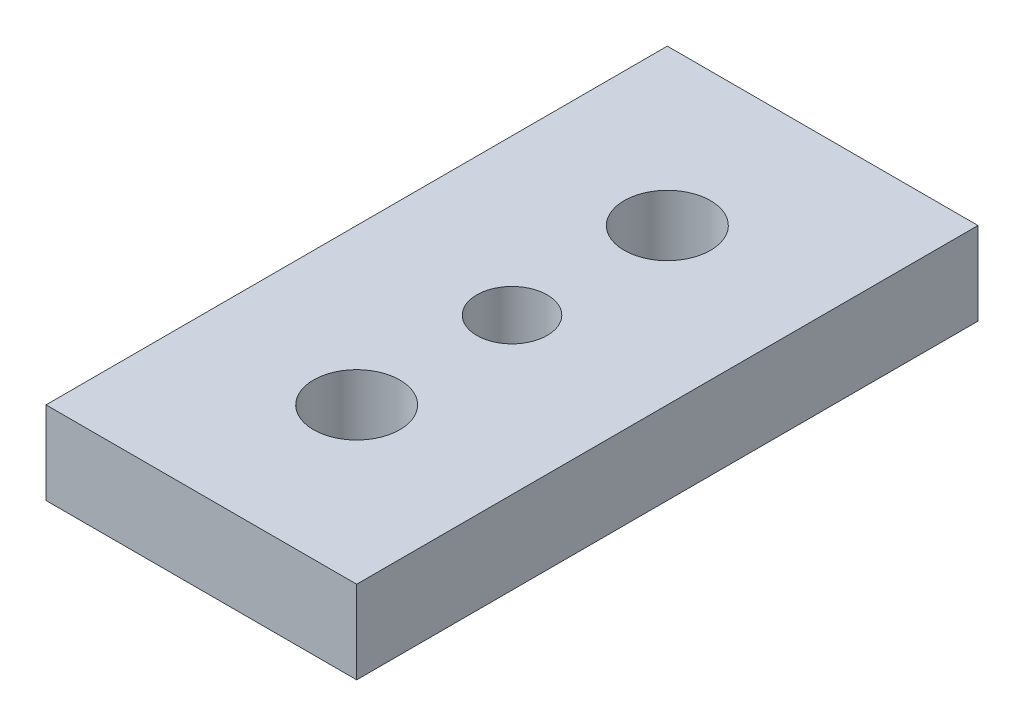
SolidWorks part; units mm, degrees
ref_plane "前视基准面" through (0, 0, 0) normal (0, 0, 1) x (1, 0, 0)
ref_plane "上视基准面" through (0, 0, 0) normal (0, 1, 0) x (1, 0, 0)
ref_plane "右视基准面" through (0, 0, 0) normal (1, 0, 0) x (0, 0, -1)
sketch "草图1" plane through (0, 0, 0) normal (0, 1, 0) x (1, 0, 0)
  line B0 (0, 0) -> (45, 0)
  line B1 (45, 0) -> (45, 90)
  line B2 (45, 90) -> (0, 90)
  line B3 (0, 90) -> (0, 0)
  circle B4 centre (22.5, 67.5) radius 6.25
  circle B5 centre (22.5, 22.5) radius 6.25
sketch_block_instance "A$C5C6430CE-1"
sketch_block "A$C5C6430CE"
extrude "凸台-拉伸1" add sketch "草图1" along normal blind 12
sketch "草图3" plane through (0, 12, 0) normal (0, 1, 0) x (1, 0, 0)
  point P0 (22.5, 45)
hole_wizard "M12 螺纹孔1" positions "3D草图1" profile "草图4" tap size "M12" standard "Iso"
sketch3d "3D草图1"
  point P0 (22.5, 12, -45)
sketch "草图4" plane through (22.5, 12, -45) normal (1, 0, 0) x (0, 0, 1)
  line L0 (0, 0) -> (0, 32.3144)
  line L1 (0, 32.3144) -> (5.1, 29.25)
  line L2 (5.1, 29.25) -> (5.1, 0)
  line L5 (5.1, 0) -> (0, 0)
  line L10 (0, 32.3144) -> (-5.1, 29.25) construction
  line L11 (0, -6.35) -> (0, 107.95) construction
  dimension "螺纹孔钻头直径" = 10.2
  dimension "螺纹孔钻头深度" = 29.25
  dimension "导头角度" = 118
cosmetic thread "孔螺蚊线1" parameters "D1"=12, "D2"=12
